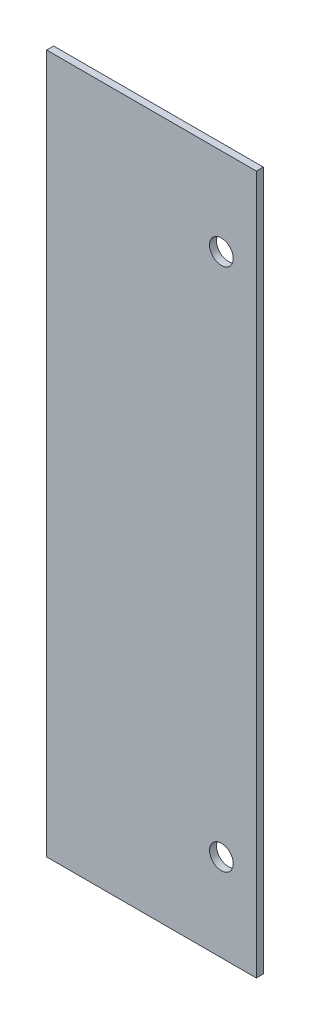
SolidWorks part; units mm, degrees
ref_plane "Front Plane" through (0, 0, 0) normal (0, 0, 1) x (1, 0, 0)
ref_plane "Top Plane" through (0, 0, 0) normal (0, 1, 0) x (1, 0, 0)
ref_plane "Right Plane" through (0, 0, 0) normal (1, 0, 0) x (0, 0, -1)
sketch "Sketch1" plane through (0, 0, 0) normal (0, 0, 1) x (1, 0, 0)
  line L1 (-15, -50) -> (15, -50)
  line L2 (-15, -50) -> (-15, 50)
  line L3 (-15, 50) -> (15, 50)
  line L4 (15, -50) -> (15, 50)
  line L5 (-15, -50) -> (15, 50) construction
  line L6 (-15, 50) -> (15, -50) construction
  point P0 (0, 0)
extrude "Boss-Extrude1" add sketch "Sketch1" against normal blind 1
sketch "Sketch2" plane through (0, 0, 0) normal (0, 0, 1) x (1, 0, 0)
  circle A0 centre (10, -37.5) radius 1.7
  circle A1 centre (10, 37.5) radius 1.7
extrude "Cut-Extrude1" cut sketch "Sketch2" along normal through all and the other way through all
